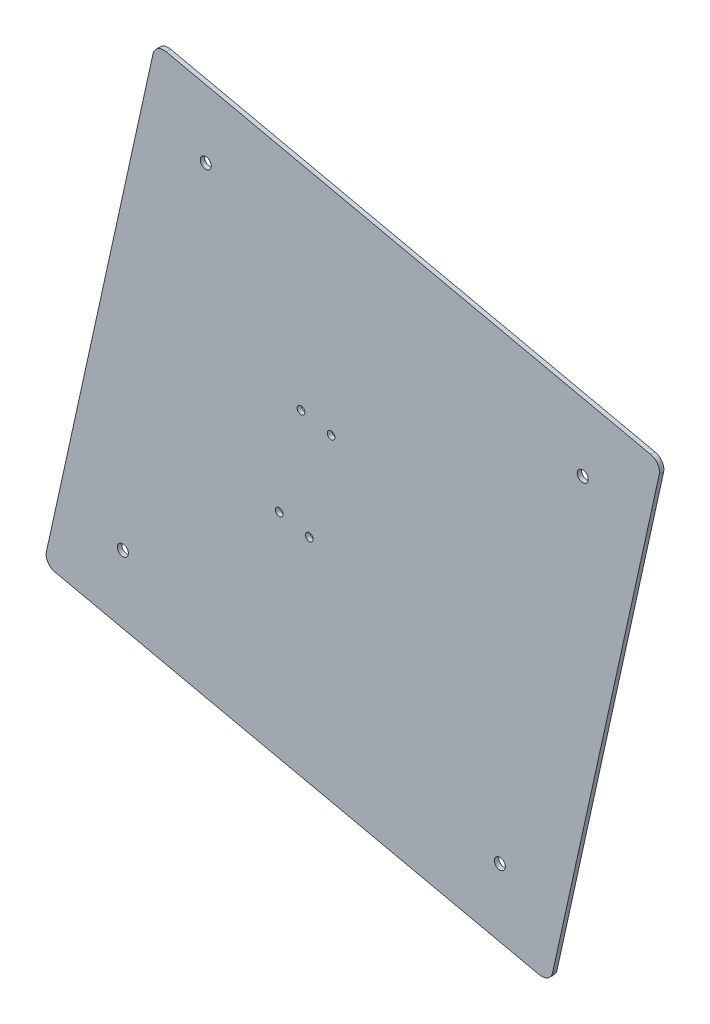
SolidWorks part; units mm, degrees
ref_plane "Plan de face" through (0, 0, 0) normal (0, 0, 1) x (1, 0, 0)
ref_plane "Plan de dessus" through (0, 0, 0) normal (0, 1, 0) x (1, 0, 0)
ref_plane "Plan de droite" through (0, 0, 0) normal (1, 0, 0) x (0, 0, -1)
sketch "Esquisse1" plane through (0, 0, 0) normal (0, 0, 1) x (1, 0, 0)
  line L8 (-201.7754, 13.6632) -> (17.9719, -34.67)
  line L9 (-157.2514, 239.3679) -> (-205.5846, 19.6205)
  line L10 (68.4533, 194.8439) -> (-151.2941, 243.1771)
  line L11 (23.9293, -30.8608) -> (72.2625, 188.8866)
  circle A0 centre (-100.0322, 88.0437) radius 1.75 construction
  circle A1 centre (-86.359, 85.0363) radius 1.75 construction
  circle A2 centre (-133.3221, 208.5071) radius 2.5
  circle A3 centre (-76.4776, 129.9625) radius 1.75 construction
  circle A4 centre (-170.9146, 37.5925) radius 2.5
  circle A5 centre (-90.1508, 132.9699) radius 1.75 construction
  circle A6 centre (0, 0) radius 2.5
  circle A7 centre (-100.0322, 88.0437) radius 1.75
  circle A8 centre (37.5925, 170.9146) radius 2.5
  circle A9 centre (-86.359, 85.0363) radius 1.75
  circle A10 centre (-76.4776, 129.9625) radius 1.75
  circle A11 centre (-90.1508, 132.9699) radius 1.75
  arc A16 (-205.5846, 19.6205) -> (-201.7754, 13.6632) centre (-200.7013, 18.5465) ccw
  arc A17 (-151.2941, 243.1771) -> (-157.2514, 239.3679) centre (-152.3681, 238.2938) ccw
  arc A18 (72.2625, 188.8866) -> (68.4533, 194.8439) centre (67.3792, 189.9606) ccw
  arc A19 (17.9719, -34.67) -> (23.9293, -30.8608) centre (19.046, -29.7867) ccw
extrude "Boss.-Extru.1" add sketch "Esquisse1" along normal blind 2
